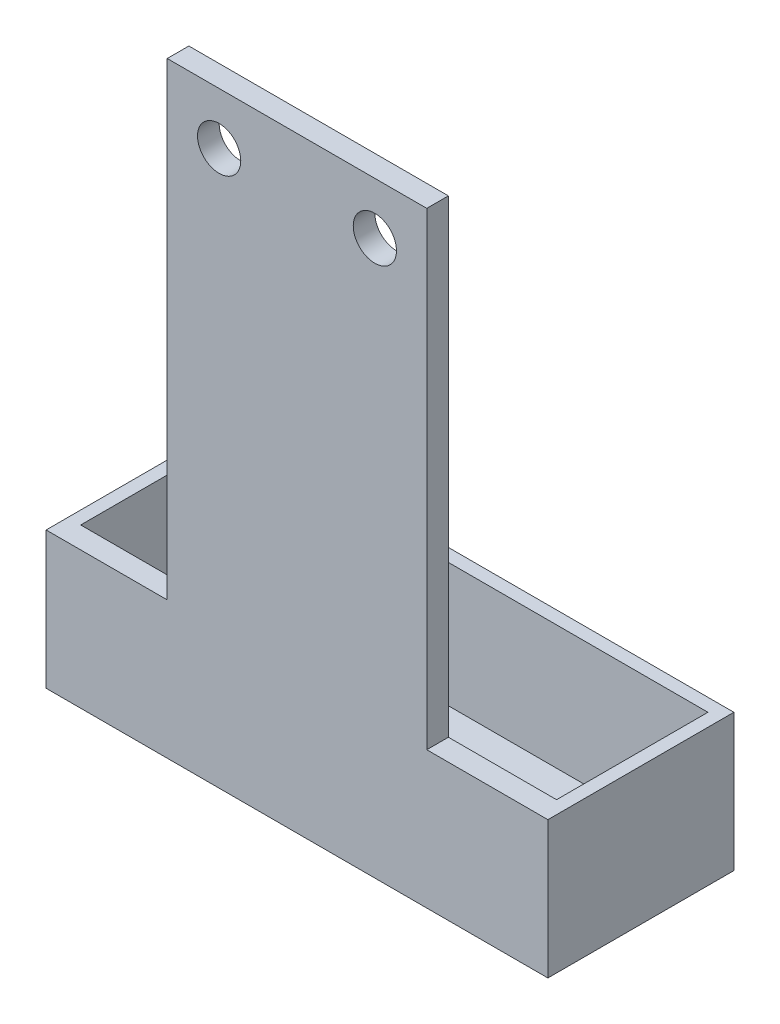
SolidWorks part; units mm, degrees
ref_plane "前视基准面" through (0, 0, 0) normal (0, 0, 1) x (1, 0, 0)
ref_plane "上视基准面" through (0, 0, 0) normal (0, 1, 0) x (1, 0, 0)
ref_plane "右视基准面" through (0, 0, 0) normal (1, 0, 0) x (0, 0, -1)
sketch "草图2" plane through (0, 0, 0) normal (0, 0, 1) x (1, 0, 0)
  line L0 (17.1371, 52.5352) -> (17.1371, 57.5469) construction
  line L1 (-55.0629, -49.8309) -> (-52.1419, -28.7682) construction
  line L2 (-50.3107, -18.6945) -> (-42.7752, 14.7138) construction
  line L3 (-36.7696, 26.4745) -> (-19.991, 45.5119) construction
  line L4 (-17.1371, 53.0659) -> (-17.1371, 57.5469) construction
  line L5 (36.7573, 26.4745) -> (19.9786, 45.5119) construction
  line L6 (50.2983, -18.6945) -> (42.7629, 14.7138) construction
  line L7 (55.0505, -49.8309) -> (52.1296, -28.7682) construction
  line L8 (-88.1866, -80.276) -> (-88.1866, -95.9665) construction
  line L9 (-88.1866, -95.9665) -> (88.1742, -95.9665) construction
  line L10 (88.1742, -80.276) -> (88.1742, -95.9665) construction
  line L11 (-30.0062, -35.9665) -> (29.9938, -35.9665)
  line L12 (-30.0062, -35.9665) -> (-30.0062, -144.3565)
  line L14 (29.9938, -35.9665) -> (29.9938, -144.3565)
  line L15 (-0.0062, -116.2673) -> (-0.0062, -144.3565) construction
  line L16 (-0.0062, -176.0565) -> (-0.0062, -1214.7116) construction
  line L17 (57.9938, -144.3565) -> (29.9938, -144.3565)
  line L18 (57.9938, -144.3565) -> (57.9938, -176.0565)
  line L19 (57.9938, -176.0565) -> (-58.0062, -176.0565)
  line L20 (-58.0062, -144.3565) -> (-58.0062, -176.0565)
  line L21 (-30.0062, -144.3565) -> (-58.0062, -144.3565)
  arc A0 (47.9392, 76.0281) -> (17.1371, 57.5469) centre (38.0826, 57.5469) ccw construction
  arc A1 (77.2252, 52.5796) -> (47.9392, 76.0281) centre (0, -13.8579) ccw construction
  arc A2 (112.9711, 60.4031) -> (-112.9711, 60.4031) centre (0, 14.704) ccw construction
  arc A3 (-47.9392, 76.0281) -> (-77.2252, 52.5796) centre (0, -13.8579) ccw construction
  arc A4 (-17.1371, 57.5469) -> (-47.9392, 76.0281) centre (-38.0826, 57.5469) ccw construction
  arc A5 (-75.8097, -67.8992) -> (-55.0629, -49.8309) centre (-75.8097, -46.9538) ccw construction
  arc A6 (-52.1419, -28.7682) -> (-50.3107, -18.6945) centre (68.5671, -45.508) cw construction
  arc A7 (-42.7752, 14.7138) -> (-36.7696, 26.4745) centre (-16.7707, 8.8484) cw construction
  arc A8 (-19.991, 45.5119) -> (-17.1371, 53.0659) centre (-28.5619, 53.0659) ccw construction
  arc A9 (19.9786, 45.5119) -> (17.1371, 52.5352) centre (28.5496, 53.0659) cw construction
  arc A10 (36.7573, 26.4745) -> (42.7629, 14.7138) centre (16.7584, 8.8484) cw construction
  arc A11 (52.1296, -28.7682) -> (50.2983, -18.6945) centre (-68.5794, -45.508) ccw construction
  arc A12 (75.7974, -67.8992) -> (55.0505, -49.8309) centre (75.7974, -46.9538) cw construction
  arc A13 (-88.1866, -80.276) -> (-75.8097, -67.8992) centre (-75.8097, -80.276) cw construction
  arc A14 (88.1742, -80.276) -> (75.7974, -67.8992) centre (75.7974, -80.276) ccw construction
  spline S0 degree 3 poles (77.2252, 52.5796) (77.3969, 52.3799) (77.7155, 51.9908) (78.4379, 51.0349) (79.3895, 49.6395) (80.6051, 47.6961) (82.3088, 44.8631) (84.6189, 41.0374) (87.4226, 37.2179) (90.2348, 34.3205) (92.6584, 32.2924) (95.3961, 30.4631) (98.4437, 28.8524) (101.2381, 27.6855) (103.3665, 26.9412) (104.3709, 26.6187) (104.8665, 26.4657) (105.1388, 26.3823) (105.6358, 26.2298) (106.335, 26.0154) (107.4598, 25.6703) (109.4254, 25.0675) (111.1111, 24.5504) (112.2347, 24.2057) knots 0 0 0 0 0.036189 0.072379 0.144757 0.217136 0.289514 0.434271 0.579028 0.651407 0.723786 0.796164 0.868543 0.940921 0.97711 0.995205 0.999729 1.004252 1.0133 1.031394 1.049489 1.085678 1.158057 1.158057 1.158057 1.158057 construction
  spline S1 degree 3 poles (112.2347, 24.2057) (112.4686, 24.9988) (112.8195, 26.1885) (113.2872, 27.7748) (113.6381, 28.9642) (113.9305, 29.9562) (114.1642, 30.7481) (114.3109, 31.2468) (114.4268, 31.6372) (114.5785, 32.1638) (114.8092, 33.02) (115.225, 34.7689) (115.6524, 37.2101) (115.9475, 40.0712) (116.0533, 42.8302) (115.984, 46.3519) (115.5744, 50.4139) (114.9088, 53.9109) (114.3152, 56.3078) (113.8592, 57.8941) (113.4855, 59.0321) (113.1908, 59.8453) (113.0471, 60.2151) (112.9711, 60.4031) knots 0 0 0 0 0.077543 0.116314 0.155085 0.193857 0.213242 0.232628 0.242321 0.252014 0.271399 0.310171 0.387713 0.465256 0.542799 0.620341 0.775427 0.930512 1.008055 1.085598 1.16314 1.201912 1.240683 1.240683 1.240683 1.240683 construction
  spline S2 degree 3 poles (-112.9711, 60.4031) (-113.0471, 60.2151) (-113.1908, 59.8453) (-113.4855, 59.0321) (-113.8592, 57.8941) (-114.3152, 56.3078) (-114.9088, 53.9109) (-115.5744, 50.4139) (-115.984, 46.3519) (-116.0533, 42.8302) (-115.9475, 40.0712) (-115.6524, 37.2101) (-115.225, 34.7689) (-114.8092, 33.02) (-114.5785, 32.1638) (-114.4268, 31.6372) (-114.3109, 31.2468) (-114.1642, 30.7481) (-113.9305, 29.9562) (-113.6381, 28.9642) (-113.2872, 27.7748) (-112.8195, 26.1885) (-112.4686, 24.9988) (-112.2347, 24.2057) knots 0 0 0 0 0.038771 0.077543 0.155085 0.232628 0.310171 0.465256 0.620341 0.697884 0.775427 0.852969 0.930512 0.969283 0.988669 0.998362 1.008055 1.02744 1.046826 1.085598 1.124369 1.16314 1.240683 1.240683 1.240683 1.240683 construction
  spline S3 degree 3 poles (-112.2347, 24.2057) (-111.1111, 24.5504) (-109.4254, 25.0675) (-107.4598, 25.6703) (-106.335, 26.0154) (-105.6358, 26.2298) (-105.1388, 26.3823) (-104.8665, 26.4657) (-104.3709, 26.6187) (-103.3665, 26.9412) (-101.2381, 27.6855) (-98.4437, 28.8524) (-95.3961, 30.4631) (-92.6584, 32.2924) (-90.2348, 34.3205) (-87.4226, 37.2179) (-84.6189, 41.0374) (-82.3088, 44.8631) (-80.6051, 47.6961) (-79.3895, 49.6395) (-78.4379, 51.0349) (-77.7155, 51.9908) (-77.3969, 52.3799) (-77.2252, 52.5796) knots 0 0 0 0 0.072379 0.108568 0.126662 0.144757 0.153804 0.158328 0.162852 0.180946 0.217136 0.289514 0.361893 0.434271 0.50665 0.579028 0.723786 0.868543 0.940921 1.0133 1.085678 1.121868 1.158057 1.158057 1.158057 1.158057 construction
  dimension "D1" = 30
  dimension "D2" = 30
  dimension "D3" = 60
  dimension "D5" = 116
  dimension "D6" = 31.7
extrude "凸台-拉伸1" add sketch "草图2" along normal blind 5
sketch "草图3" plane through (0, 0, 0) normal (0, 0, -1) x (-1, 0, 0)
  line L0 (-57.9938, -144.3565) -> (-57.9938, -176.0565)
  line L1 (-57.9938, -176.0565) -> (58.0062, -176.0565)
  line L2 (58.0062, -176.0565) -> (58.0062, -144.3565)
  line L3 (58.0062, -144.3565) -> (55.0062, -144.3565)
  line L4 (30.0062, -144.3565) -> (58.0062, -144.3565) construction
  line L5 (55.0062, -144.3565) -> (55.0062, -173.0565)
  line L6 (55.0062, -173.0565) -> (-54.9938, -173.0565)
  line L7 (-54.9938, -173.0565) -> (-54.9938, -144.3565)
  line L8 (-57.9938, -144.3565) -> (-29.9938, -144.3565) construction
  line L9 (-54.9938, -144.3565) -> (-57.9938, -144.3565)
  dimension "D1" = 3
  dimension "D2" = 3
  dimension "D3" = 3
extrude "凸台-拉伸2" add sketch "草图3" along normal blind 35
sketch "草图4" plane through (0, 0, -35) normal (0, 0, -1) x (-1, 0, 0)
  line L0 (58.0062, -176.0565) -> (58.0062, -144.3565) construction
  line L1 (-57.9938, -144.3565) -> (58.0062, -144.3565)
  line L2 (-57.9938, -144.3565) -> (-57.9938, -176.0565)
  line L3 (-57.9938, -176.0565) -> (58.0062, -176.0565)
  line L4 (58.0062, -144.3565) -> (58.0062, -176.0565)
  line L5 (-57.9938, -176.0565) -> (58.0062, -176.0565) construction
extrude "凸台-拉伸3" add sketch "草图4" along normal blind 3
sketch "草图6" plane through (0, 0, 0) normal (0, 0, -1) x (-1, 0, 0)
  line L0 (0.0062, -35.9665) -> (0.0062, -84.3789) construction
  line L2 (-29.9938, -35.9665) -> (30.0062, -35.9665) construction
  line L3 (-29.9938, -144.3565) -> (-29.9938, -35.9665) construction
  line L4 (30.0062, -35.9665) -> (30.0062, -144.3565) construction
  circle A0 centre (-17.9938, -47.9665) radius 5
  circle A1 centre (18.0062, -47.9665) radius 5
  dimension "D1" = 12
  dimension "D3" = 10
  dimension "D2" = 12
extrude "切除-拉伸1" cut sketch "草图6" against normal through all
